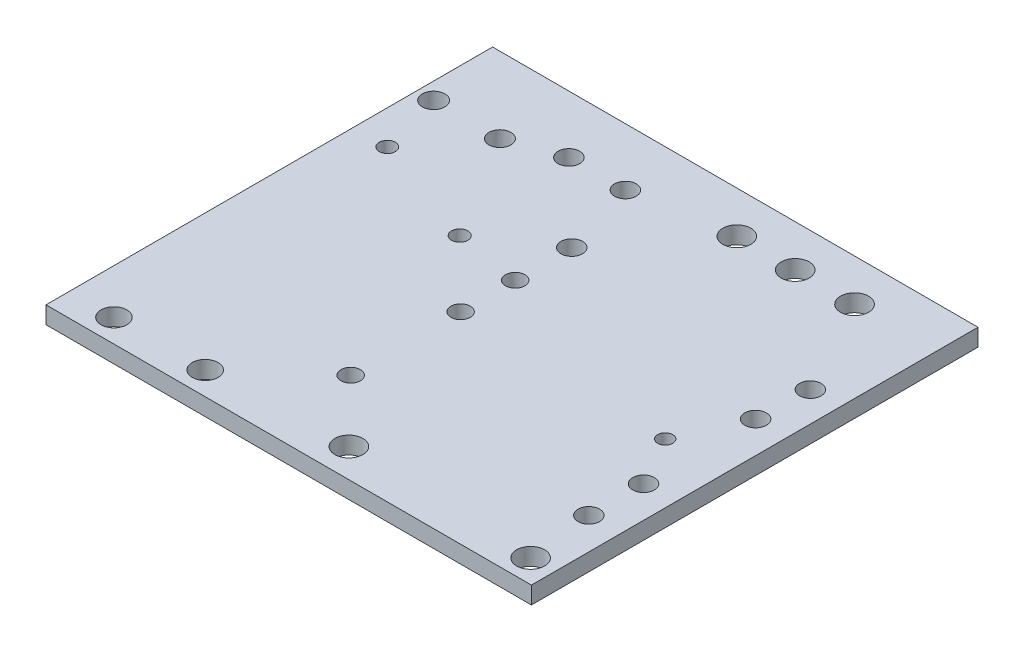
SolidWorks part; units mm, degrees
ref_plane "Plano frontal" through (0, 0, 0) normal (0, 0, 1) x (1, 0, 0)
ref_plane "Plano superior" through (0, 0, 0) normal (0, 1, 0) x (1, 0, 0)
ref_plane "Plano direito" through (0, 0, 0) normal (1, 0, 0) x (0, 0, -1)
sketch "Esboço1" plane through (0, 0, 0) normal (0, 1, 0) x (1, 0, 0)
  line L1 (-11.25, -10.35) -> (11.25, -10.35)
  line L2 (-11.25, -10.35) -> (-11.25, 10.35)
  line L3 (-11.25, 10.35) -> (11.25, 10.35)
  line L4 (11.25, -10.35) -> (11.25, 10.35)
  line L5 (-11.25, -10.35) -> (11.25, 10.35) construction
  line L6 (-11.25, 10.35) -> (11.25, -10.35) construction
  point P0 (0, 0)
  dimension "D1" = 22.5
  dimension "D2" = 20.7
extrude "Ressalto-extrusão1" add sketch "Esboço1" along normal blind 0.8
sketch "Esboço2" plane through (0, 0.8, 0) normal (0, 1, 0) x (1, 0, 0)
  circle A0 centre (-1.3625, 4.1322) radius 0.5
  circle A1 centre (9.782, 1.5102) radius 0.5
  circle A2 centre (9.782, -3.6844) radius 0.5
  circle A3 centre (9.782, -6.2204) radius 0.5
  circle A4 centre (10.1406, -9.2769) radius 0.65
  circle A5 centre (1.4565, -9.0184) radius 0.65
  circle A6 centre (-5.0491, 7.6843) radius 0.5
  circle A7 centre (-2.4299, 7.6843) radius 0.5
  circle A8 centre (-1.3625, -6.114) radius 0.45
  circle A9 centre (9.8683, 3.961) radius 0.5
  circle A10 centre (-1.3625, 1.5102) radius 0.45
  circle A11 centre (-1.3625, -1.0188) radius 0.45
  circle A12 centre (2.0098, 8.4128) radius 0.65
  circle A13 centre (4.7134, 8.4128) radius 0.65
  circle A14 centre (7.4645, 8.4128) radius 0.65
  circle A15 centre (-7.4006, 6.8402) radius 0.507
  circle A16 centre (-9.1732, -9.2769) radius 0.6
  circle A17 centre (-4.9457, -9.2769) radius 0.6
  circle A18 centre (-9.6779, 3.897) radius 0.3757
  circle A19 centre (-4.4414, 2.0176) radius 0.3788
  circle A20 centre (8.4857, -1.3841) radius 0.35
  circle A21 centre (-10.4732, 6.8402) radius 0.523
  dimension "D1" = 1
  dimension "D2" = 1
  dimension "D3" = 1
  dimension "D4" = 1
  dimension "D5" = 1
  dimension "D6" = 1.3
  dimension "D7" = 1.3
  dimension "D8" = 1
  dimension "D9" = 0.9
  dimension "D10" = 1
  dimension "D11" = 0.9
  dimension "D12" = 0.9
  dimension "D13" = 1.3
  dimension "D14" = 1.2
  dimension "D15" = 1.2
extrude "Corte-extrusão1" cut sketch "Esboço2" against normal blind 2
